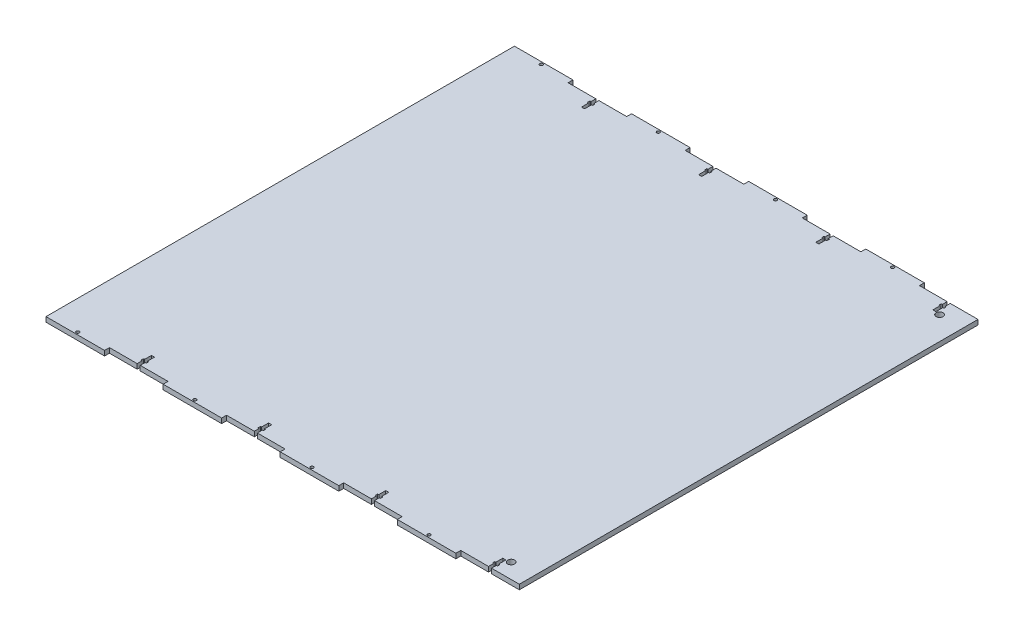
SolidWorks part; units mm, degrees
material "Acrylic (Medium-high impact)"
ref_plane "Front Plane" through (0, 0, 0) normal (0, 0, 1) x (1, 0, 0)
ref_plane "Top Plane" through (0, 0, 0) normal (0, 1, 0) x (1, 0, 0)
ref_plane "Right Plane" through (0, 0, 0) normal (1, 0, 0) x (0, 0, -1)
sketch "Sketch1" plane through (0, 0, 0) normal (0, 1, 0) x (1, 0, 0)
  line L0 (-304.8, 0) -> (304.8, 0)
  line L1 (-304.8, -304.8) -> (304.8, -304.8)
  line L2 (-304.8, -304.8) -> (-304.8, 304.8)
  line L3 (-304.8, 304.8) -> (304.8, 304.8)
  line L4 (304.8, -304.8) -> (304.8, 304.8)
  line L5 (-304.8, -304.8) -> (304.8, 304.8) construction
  line L6 (-304.8, 304.8) -> (304.8, -304.8) construction
  point P0 (0, 0)
  dimension "D1" = 609.6
  dimension "D2" = 609.6
extrude "Boss-Extrude1" add sketch "Sketch1" along normal mid plane 6.35 contours L1 L4 L0 L2
sketch "Sketch2" plane through (0, 3.175, 0) normal (0, 1, 0) x (1, 0, 0)
  line L10 (-228.6, -304.8) -> (-152.4, -304.8)
  line L11 (-228.6, -304.8) -> (-228.6, -298.45)
  line L12 (-228.6, -298.45) -> (-152.4, -298.45)
  line L13 (-152.4, -304.8) -> (-152.4, -298.45)
  line L14 (-304.8, -304.8) -> (304.8, -304.8) construction
  line L15 (-76.2, -304.8) -> (0, -304.8)
  line L16 (-76.2, -304.8) -> (-76.2, -298.45)
  line L17 (-76.2, -298.45) -> (0, -298.45)
  line L18 (0, -304.8) -> (0, -298.45)
  line L19 (-304.8, -304.8) -> (-304.8, 0) construction
  line L20 (76.2, -304.8) -> (152.4, -304.8)
  line L21 (76.2, -304.8) -> (76.2, -298.45)
  line L22 (76.2, -298.45) -> (152.4, -298.45)
  line L23 (152.4, -304.8) -> (152.4, -298.45)
  line L24 (228.6, -304.8) -> (304.8, -304.8)
  line L25 (228.6, -304.8) -> (228.6, -298.45)
  line L26 (228.6, -298.45) -> (304.8, -298.45)
  line L27 (304.8, -304.8) -> (304.8, -298.45)
  line L28 (-192.5, -298.45) -> (-192.5, -292.05)
  line L29 (-192.5, -292.05) -> (-193.89, -292.05)
  line L30 (-193.89, -292.05) -> (-193.89, -288.85)
  line L31 (-193.89, -288.85) -> (-192.5, -288.85)
  line L32 (-192.5, -288.85) -> (-192.5, -279.8)
  line L33 (-192.5, -279.8) -> (-188.5, -279.8)
  line L34 (-188.5, -279.8) -> (-188.5, -288.85)
  line L35 (-188.5, -288.85) -> (-187.11, -288.85)
  line L36 (-187.11, -288.85) -> (-187.11, -292.05)
  line L37 (-187.11, -292.05) -> (-188.5, -292.05)
  line L38 (-188.5, -292.05) -> (-188.5, -298.45)
  line L39 (-190.5, -279.8) -> (-190.5, -298.45) construction
  line L40 (-40.1, -292.05) -> (-41.49, -292.05)
  line L41 (-41.49, -292.05) -> (-41.49, -288.85)
  line L42 (-41.49, -288.85) -> (-40.1, -288.85)
  line L43 (-40.1, -288.85) -> (-40.1, -279.8)
  line L44 (-40.1, -279.8) -> (-36.1, -279.8)
  line L45 (-36.1, -279.8) -> (-36.1, -288.85)
  line L46 (-36.1, -288.85) -> (-34.71, -288.85)
  line L47 (-34.71, -288.85) -> (-34.71, -292.05)
  line L48 (-34.71, -292.05) -> (-36.1, -292.05)
  line L49 (-40.1, -298.45) -> (-40.1, -292.05)
  line L50 (-36.1, -292.05) -> (-36.1, -298.45)
  line L51 (-38.1, -279.8) -> (-38.1, -298.45) construction
  line L52 (112.3, -292.05) -> (110.91, -292.05)
  line L53 (110.91, -292.05) -> (110.91, -288.85)
  line L54 (110.91, -288.85) -> (112.3, -288.85)
  line L55 (112.3, -288.85) -> (112.3, -279.8)
  line L56 (112.3, -279.8) -> (116.3, -279.8)
  line L57 (116.3, -279.8) -> (116.3, -288.85)
  line L58 (116.3, -288.85) -> (117.69, -288.85)
  line L59 (117.69, -288.85) -> (117.69, -292.05)
  line L60 (117.69, -292.05) -> (116.3, -292.05)
  line L61 (112.3, -298.45) -> (112.3, -292.05)
  line L62 (116.3, -292.05) -> (116.3, -298.45)
  line L63 (114.3, -279.8) -> (114.3, -298.45) construction
  line L64 (264.7, -292.05) -> (263.31, -292.05)
  line L65 (263.31, -292.05) -> (263.31, -288.85)
  line L66 (263.31, -288.85) -> (264.7, -288.85)
  line L67 (264.7, -288.85) -> (264.7, -279.8)
  line L68 (264.7, -279.8) -> (268.7, -279.8)
  line L69 (268.7, -279.8) -> (268.7, -288.85)
  line L70 (268.7, -288.85) -> (270.09, -288.85)
  line L71 (270.09, -288.85) -> (270.09, -292.05)
  line L72 (270.09, -292.05) -> (268.7, -292.05)
  line L73 (264.7, -298.45) -> (264.7, -292.05)
  line L74 (268.7, -292.05) -> (268.7, -298.45)
  line L75 (266.7, -279.8) -> (266.7, -298.45) construction
  line L76 (304.8, -304.8) -> (304.8, 0) construction
  circle A0 centre (-266.7, -301.625) radius 2
  circle A1 centre (-114.3, -301.625) radius 2
  circle A2 centre (38.1, -301.625) radius 2
  circle A3 centre (190.5, -301.625) radius 2
  circle A4 centre (274.46, -278.775) radius 4.5
  point P22 (-76.2, -301.625)
  line M22 (-304.8, -304.8) -> (304.8, -304.8)
  line M23 (304.8, -304.8) -> (304.8, 0)
  dimension "D10" = 4
  dimension "D19" = 9
  dimension "D1" = 76.2
  dimension "D2" = 76.2
  dimension "D3" = 76.2
  dimension "D4" = 76.2
  dimension "D5" = 76.2
  dimension "D6" = 76.2
  dimension "D7" = 76.2
  dimension "D8" = 6.35
  dimension "D9" = 76.2
  dimension "D11" = 3.175
  dimension "D12" = 38.1
  dimension "D13" = 4
  dimension "D14" = 6.78
  dimension "D15" = 3.2
  dimension "D16" = 6.4
  dimension "D17" = 18.65
  dimension "D18" = 38.1
  dimension "D20" = 19.675
  dimension "D21" = 30.34
extrude "Cut-Extrude1" cut sketch "Sketch2" along direction (0, 1, 0) on the side against the normal through all both and the other way through all contours A0 | L13 L12 L11 M22 | L38 L37 L36 L35 L34 L33 L32 L31 L30 L29 L28 L12 | A1 | L18 L17 L16 M22 | L50 L48 L47 L46 L45 L44 L43 L42 L41 L40 L49 L17 | A2 | L23 L22 L21 M22 | L62 L60 L59 L58 L57 L56 L55 L54 L53 L52 L61 L22 | A3 | L26 L25 M22 M23 | L74 L72 L71 L70 L69 L68 L67 L66 L65 L64 L73 L26 | A4
mirror "Mirror1" about plane through (0, 3.175, 0) normal (0, 0, -1) of "Cut-Extrude1", "Boss-Extrude1"
